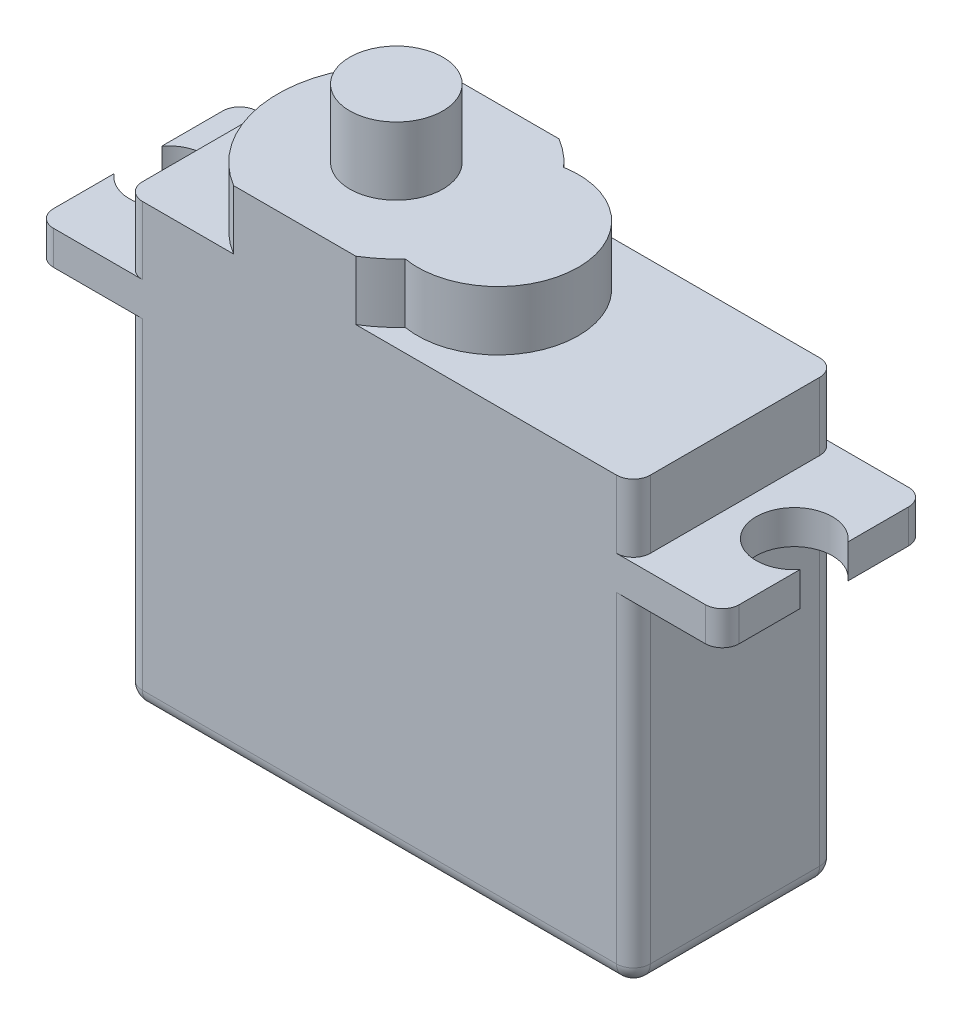
SolidWorks part; units mm, degrees
ref_plane "Front" through (0, 0, 0) normal (0, 0, 1) x (1, 0, 0)
ref_plane "Top" through (0, 0, 0) normal (0, 1, 0) x (1, 0, 0)
ref_plane "Right" through (0, 0, 0) normal (1, 0, 0) x (0, 0, -1)
sketch "Sketch1" plane through (0, 0, 0) normal (0, 1, 0) x (1, 0, 0)
  line L1 (-15, -6) -> (15, -6)
  line L2 (-15, -6) -> (-15, 6)
  line L3 (-15, 6) -> (15, 6)
  line L4 (15, -6) -> (15, 6)
  line L5 (-15, -6) -> (15, 6) construction
  line L6 (-15, 6) -> (15, -6) construction
  point P0 (0, 0)
  dimension "D1" = 30
  dimension "D2" = 12
extrude "Boss-Extrude1" add sketch "Sketch1" along normal blind 20
sketch "Sketch2" plane through (0, 20, 0) normal (0, 1, 0) x (1, 0, 0)
  line L0 (-20.25, 0) -> (20.25, 0) construction
  line L1 (-20.25, 6) -> (20.25, 6)
  line L2 (-20.25, 6) -> (-20.25, 1.4142)
  line L3 (-20.25, -6) -> (20.25, -6)
  line L4 (20.25, 6) -> (20.25, 1.4142)
  line L5 (-20.25, 6) -> (20.25, -6) construction
  line L6 (-20.25, -6) -> (20.25, 6) construction
  line L7 (0, 6) -> (0, -6) construction
  line L8 (-15, 6) -> (-15, -6) construction
  line L9 (-20.25, -1.4142) -> (-20.25, -6)
  line L10 (20.25, -1.4142) -> (20.25, -6)
  arc A0 (-20.25, -1.4142) -> (-20.25, 1.4142) centre (-18.5, 0) ccw
  arc A1 (20.25, -1.4142) -> (20.25, 1.4142) centre (18.5, 0) cw
  point P0 (0, 0)
  dimension "D3" = 4.5
  dimension "D2" = 12
  dimension "D4" = 3.5
  dimension "D5" = 40.5
extrude "Boss-Extrude2" add sketch "Sketch2" along normal blind 2
sketch "Sketch3" plane through (0, 22, 0) normal (0, 1, 0) x (1, 0, 0)
  line L0 (-20.25, -6) -> (20.25, -6) construction
  line L1 (-15, 6) -> (15, 6)
  line L2 (-15, 6) -> (-15, -6)
  line L3 (-15, -6) -> (15, -6)
  line L4 (15, 6) -> (15, -6)
  line L5 (-15, 6) -> (15, -6) construction
  line L6 (-15, -6) -> (15, 6) construction
  point P0 (0, 0)
  dimension "D1" = 30
extrude "Boss-Extrude3" add sketch "Sketch3" along normal blind 4
sketch "Sketch4" plane through (0, 26, 0) normal (0, 1, 0) x (1, 0, 0)
  line L0 (-18.5, 0) -> (18.5063, 0) construction
  line L1 (-5, 6) -> (-5, -6) construction
  line L2 (15, 6) -> (-15, 6) construction
  line L3 (-15, -6) -> (15, -6) construction
  line L4 (-15, 6) -> (-15, -6) construction
  line L5 (-15, 6) -> (-15, -6) construction
  line L6 (-8.6056, 6) -> (-1.3944, 6)
  line L7 (-8.6056, -6) -> (-1.3944, -6)
  arc A0 (-8.6056, 6) -> (-8.6056, -6) centre (-5, 0) ccw
  arc A1 (0.2031, -4.6827) -> (0.2031, 4.6827) centre (1, 0) ccw
  arc A2 (-1.3944, -6) -> (0.2031, -4.6827) centre (-5, 0) ccw
  arc A3 (0.2031, 4.6827) -> (-1.3944, 6) centre (-5, 0) ccw
  dimension "D2" = 14
  dimension "D4" = 9.5
  dimension "D1" = 10
  dimension "D3" = 16
extrude "Boss-Extrude4" add sketch "Sketch4" along normal blind 3.5
sketch "Sketch5" plane through (0, 29.5, 0) normal (0, 1, 0) x (1, 0, 0)
  line L0 (-15, 6) -> (-15, -6) construction
  circle A0 centre (-5, 0) radius 2.75
  dimension "D2" = 5.5
  dimension "D1" = 10
extrude "Boss-Extrude5" add sketch "Sketch5" along normal blind 4
fillet "Fillet1" radius 1 16 edges at (-15, 0, 0) (0, 0, -6) (15, 0, 0) (0, 0, 6) (15, 24, -6) (15, 24, 6) (-15, 24, 6) (-15, 24, -6) (20.25, 21, 6) (20.25, 21, -6) (-20.25, 21, -6) (-20.25, 21, 6) (-15, 10, -6) (15, 10, -6) (15, 10, 6) (-15, 10, 6)
